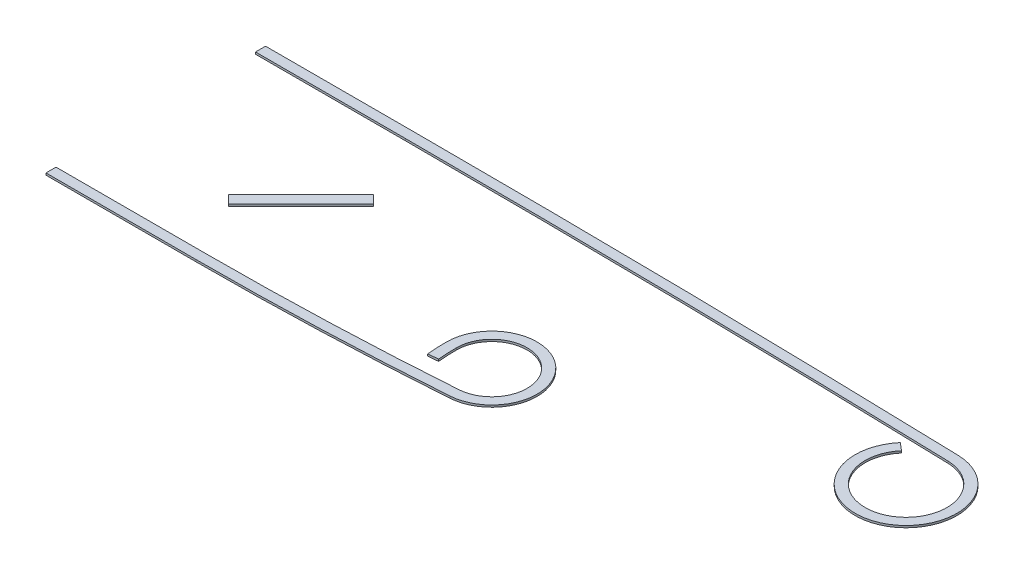
SolidWorks part; units mm, degrees
ref_plane "Front Plane" through (0, 0, 0) normal (0, 0, 1) x (1, 0, 0)
ref_plane "Top Plane" through (0, 0, 0) normal (0, 1, 0) x (1, 0, 0)
ref_plane "Right Plane" through (0, 0, 0) normal (1, 0, 0) x (0, 0, -1)
sketch "Sketch1" plane through (0, 0, 0) normal (0, 1, 0) x (1, 0, 0)
  line L0 (0, 57.3) -> (-75, 57.3)
  line L1 (0, 0) -> (224.4913, 0) construction
  line L2 (0, 52.3) -> (-75, 52.3)
  line L3 (-75, 57.3) -> (-75, 52.3)
  line L4 (258.6613, 41.1279) -> (254.8549, 44.37)
  line L5 (0, -47.3) -> (-75, -47.3)
  line L6 (-75, -47.3) -> (-75, -52.3)
  line L7 (0, -52.3) -> (-75, -52.3)
  line L8 (98.5459, -35.2722) -> (103.5213, -34.7763)
  line L9 (-16.0124, -20.1914) -> (20.1914, 16.0124)
  line L10 (-16.0124, -20.1914) -> (-20.1914, -16.0124)
  line L11 (20.1914, 16.0124) -> (16.0124, 20.1914)
  line L12 (-20.1914, -16.0124) -> (16.0124, 20.1914)
  line L13 (-16.0124, -20.1914) -> (16.0124, 20.1914) construction
  line L14 (20.1914, 16.0124) -> (-20.1914, -16.0124) construction
  arc A0 (103.0538, -25.3728) -> (103.5213, -34.7763) centre (197.8672, -25.3728) ccw
  arc A1 (0, 57.3) -> (274.9324, 53.2892) centre (0, -9367.7178) cw
  arc A2 (274.9324, 53.2892) -> (299.5914, 27.9) centre (274.1914, 27.9) cw
  arc A3 (299.5914, 27.9) -> (254.8549, 44.37) centre (274.1914, 27.9) cw
  arc A4 (294.5914, 27.9) -> (258.6613, 41.1279) centre (274.1914, 27.9) cw
  arc A5 (274.7865, 48.2913) -> (294.5914, 27.9) centre (274.1914, 27.9) cw
  arc A6 (0, 52.3) -> (274.7865, 48.2913) centre (0, -9367.7178) cw
  arc A7 (121.9165, -42.9301) -> (103.0538, -25.3728) centre (120.6563, -25.3728) ccw
  arc A8 (98.0538, -25.3728) -> (98.5459, -35.2722) centre (197.8672, -25.3728) ccw
  arc A9 (122.2745, -47.9173) -> (98.0538, -25.3728) centre (120.6563, -25.3728) ccw
  arc A10 (0, -47.3) -> (121.9165, -42.9301) centre (0, 1655.5706) ccw
  arc A11 (0, -52.3) -> (122.2745, -47.9173) centre (0, 1655.5706) ccw
  point P1 (98.0538, -25.3728)
  point P13 (248.7914, 27.9)
  point P14 (20.1914, 0)
  point P15 (274.1914, 2.5)
  point P17 (0, 22.3)
  point P19 (299.5914, 27.9)
  dimension "D1" = 30
  dimension "D5" = 25.4
  dimension "D2" = 5
  dimension "D3" = 75
  dimension "D4" = 228.6
  dimension "D6" = 5
  dimension "D7" = 5.91
  dimension "D8" = 45
  dimension "D9" = 51.2
  dimension "D10" = 5
extrude "Boss-Extrude1" add sketch "Sketch1" along normal mid plane 1
